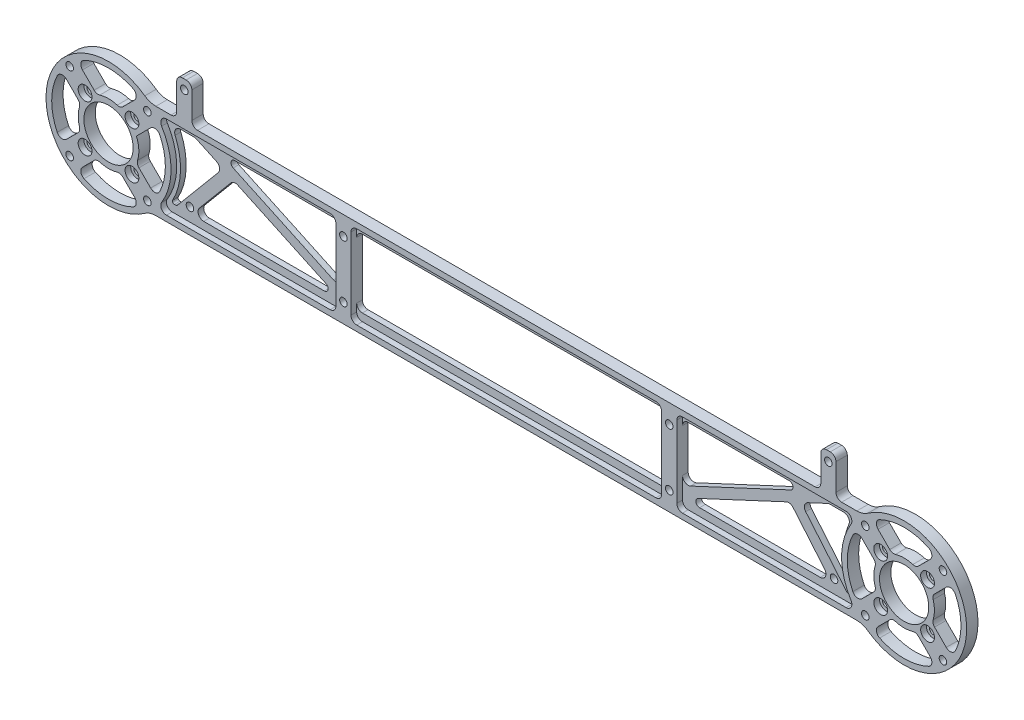
SolidWorks part; units mm, degrees
material "6061 合金"
ref_plane "前视基准面" through (0, 0, 0) normal (0, 0, 1) x (1, 0, 0)
ref_plane "上视基准面" through (0, 0, 0) normal (0, 1, 0) x (1, 0, 0)
ref_plane "右视基准面" through (0, 0, 0) normal (1, 0, 0) x (0, 0, -1)
sketch "草图1" plane through (0, 0, 0) normal (0, 0, 1) x (1, 0, 0)
  line L0 (0, 45.7031) -> (0, -72.9118) construction
  line L1 (-42.6422, 0) -> (420, 0) construction
  line L2 (0, 0) -> (-20.5061, 20.5061) construction
  line L3 (21.5407, 25) -> (398.4593, 25)
  line L4 (21.5407, -25) -> (398.4593, -25)
  line L5 (210, 25) -> (210, -95.809) construction
  line L7 (30.0167, 18) -> (120, 18)
  line L8 (30.0167, 18) -> (30.0167, -18) construction
  line L9 (30.0167, -18) -> (120, -18)
  line L10 (120, 18) -> (120, -18)
  line L11 (30.0167, 18) -> (120, -18) construction
  line L12 (30.0167, -18) -> (120, 18) construction
  line L13 (300, 18) -> (389.9833, 18)
  line L14 (300, 18) -> (300, -18)
  line L15 (300, -18) -> (389.9833, -18)
  line L16 (389.9833, 18) -> (389.9833, -18) construction
  line L17 (300, 18) -> (389.9833, -18) construction
  line L18 (300, -18) -> (389.9833, 18) construction
  line L19 (128, 18) -> (292, 18)
  line L20 (128, 18) -> (128, -18)
  line L21 (128, -18) -> (292, -18)
  line L22 (292, 18) -> (292, -18)
  line L23 (128, 18) -> (292, -18) construction
  line L24 (128, -18) -> (292, 18) construction
  circle A0 centre (0, 0) radius 29 construction
  circle A1 centre (-20.5061, 20.5061) radius 2
  circle A5 centre (20.5061, 20.5061) radius 2
  circle A6 centre (20.5061, -20.5061) radius 2
  circle A7 centre (-20.5061, -20.5061) radius 2
  circle A8 centre (0, 0) radius 13
  arc A9 (21.5407, 25) -> (21.5407, -25) centre (0, 0) ccw
  circle A10 centre (440.5061, 20.5061) radius 2
  arc A11 (398.4593, -25) -> (398.4593, 25) centre (420, 0) ccw
  circle A12 centre (420, 0) radius 13
  circle A13 centre (440.5061, -20.5061) radius 2
  circle A14 centre (399.4939, -20.5061) radius 2
  circle A15 centre (399.4939, 20.5061) radius 2
  arc A17 (389.9833, 18) -> (389.9833, -18) centre (420, 0) ccw
  arc A18 (30.0167, -18) -> (30.0167, 18) centre (0, 0) ccw
  circle A19 centre (-12.3744, 12.3744) radius 2
  circle A20 centre (12.3744, 12.3744) radius 2
  circle A21 centre (12.3744, -12.3744) radius 2
  circle A22 centre (-12.3744, -12.3744) radius 2
  circle A23 centre (432.3744, 12.3744) radius 2
  circle A24 centre (432.3744, -12.3744) radius 2
  circle A25 centre (407.6256, -12.3744) radius 2
  circle A26 centre (407.6256, 12.3744) radius 2
  point P6 (344.9917, 0)
  point P18 (0, 0)
  point P31 (75.0083, 0)
  point P42 (210, 0)
  point P58 (0, 0)
  dimension "D1" = 16
  dimension "D3" = 4
  dimension "D5" = 26
  dimension "D6" = 4
  dimension "D8" = 420
  dimension "D11" = 35
  dimension "D14" = 58
  dimension "D15" = 33
  dimension "D16" = 17.5
  dimension "D17" = 4
  dimension "D20" = 420
  dimension "D2" = 45
  dimension "D9" = 50
  dimension "D10" = 7
  dimension "D12" = 8
  dimension "D13" = 120
  dimension "D7" = 2
  dimension "D19" = 2
  dimension "D4" = 4
  dimension "D18" = 4
extrude "凸台-拉伸1" add sketch "草图1" along normal blind 6
fillet "圆角1" [suppressed] radius 3
sketch "草图2" plane through (0, 0, 6) normal (0, 0, 1) x (1, 0, 0)
  line L0 (210, 25) -> (210, -72.3198) construction
  line L1 (398.4593, 25) -> (21.5407, 25) construction
  line L2 (124, -22.0435) -> (124, 29.2031) construction
  line L3 (128, 18) -> (128, -18) construction
  line L4 (120, 0) -> (300, 0) construction
  line L5 (120, -18) -> (120, 18) construction
  line L6 (300, 18) -> (300, -18) construction
  circle A0 centre (124, 15) radius 2
  circle A1 centre (124, -15) radius 2
  circle A2 centre (296, 15) radius 2
  circle A3 centre (296, -15) radius 2
  dimension "D1" = 4
  dimension "D3" = 30
  dimension "D2" = 4
extrude "切除-拉伸1" cut sketch "草图2" against normal through all
sketch "草图3" plane through (0, 0, 6) normal (0, 0, 1) x (1, 0, 0)
  line L0 (210, -25) -> (210, 69.7704) construction
  line L1 (21.5407, -25) -> (398.4593, -25) construction
  line L2 (398.4593, 25) -> (21.5407, 25) construction
  line L3 (36, 25) -> (44, 25)
  line L4 (36, 25) -> (36, 45)
  line L5 (36, 45) -> (44, 45)
  line L6 (44, 25) -> (44, 45)
  line L7 (0, 0) -> (420, 0) construction
  line L16 (384, 25) -> (376, 25)
  line L17 (384, 25) -> (384, 45)
  line L18 (384, 45) -> (376, 45)
  line L19 (376, 25) -> (376, 45)
  line L20 (40, 45) -> (40, -45) construction
  line L21 (380, 45) -> (380, -45) construction
  line L32 (120, -12.4831) -> (54.6288, 18)
  line L33 (120, -18) -> (120, 18) construction
  line L34 (120, 18) -> (30.0167, 18) construction
  line L35 (54.6288, 18) -> (42.7978, 18)
  line L36 (42.7978, 18) -> (57.4676, 11.1593)
  line L37 (120, -18) -> (120, -12.4831)
  line L38 (57.4676, 11.1593) -> (33, -18)
  line L39 (30.0167, -18) -> (120, -18) construction
  line L40 (33, -18) -> (40.8324, -18)
  line L41 (40.8324, -18) -> (63.0973, 8.5342)
  line L43 (63.0973, 8.5342) -> (120, -18)
  line L44 (387, -18) -> (379.1676, -18)
  line L45 (362.5324, 11.1593) -> (387, -18)
  line L46 (377.2022, 18) -> (362.5324, 11.1593)
  line L47 (365.3712, 18) -> (377.2022, 18)
  line L48 (300, -12.4831) -> (365.3712, 18)
  line L49 (300, -18) -> (300, -12.4831)
  line L50 (356.9027, 8.5342) -> (300, -18)
  line L51 (379.1676, -18) -> (356.9027, 8.5342)
  circle A1 centre (380, 40) radius 2
  circle A2 centre (40, 40) radius 2
  point P31 (40, 45)
  point P32 (380, 45)
  dimension "D4" = 4
  dimension "D5" = 5
  dimension "D1" = 8
  dimension "D2" = 20
  dimension "D3" = 340
  dimension "D6" = 5
  dimension "D7" = 6
  dimension "D8" = 87
  dimension "D9" = 25
  dimension "D10" = 50
extrude "凸台-拉伸2" add sketch "草图3" against normal up to surface (6 mm away) up to face at (126, -15, 0)
fillet "圆角2" radius 3 8 edges at (36, 45, 3) (44, 45, 3) (376, 45, 3) (384, 45, 3) (376, 25, 3) (384, 25, 3) (44, 25, 3) (36, 25, 3)
sketch "草图4" plane through (0, 0, 6) normal (0, 0, 1) x (1, 0, 0)
  line L0 (40, 40) -> (40, -25) construction
  line L1 (21.5407, -25) -> (398.4593, -25) construction
  line L2 (380, 40) -> (380, -25) construction
  circle A0 centre (40, -15) radius 2
  circle A1 centre (380, -15) radius 2
  dimension "D1" = 4
  dimension "D2" = 10
extrude "切除-拉伸2" cut sketch "草图4" against normal through all
fillet "圆角3" radius 3 18 edges at (389.9833, 18, 3) (377.2022, 18, 3) (362.5324, 11.1593, 3) (379.1676, -18, 3) (356.9027, 8.5342, 3) (300, -12.4831, 3) (300, 18, 3) (292, 18, 3) (292, -18, 3) (128, 18, 3) (128, -18, 3) (120, -12.4831, 3) (120, 18, 3) (63.0973, 8.5342, 3) (57.4676, 11.1593, 3) (42.7978, 18, 3) (30.0167, 18, 3) (40.8324, -18, 3)
fillet "圆角4" radius 2 4 edges at (300, -18, 3) (365.3712, 18, 3) (54.6288, 18, 3) (120, -18, 3)
sketch "草图9" plane through (0, 0, 6) normal (0, 0, 1) x (1, 0, 0)
  line L2 (373, 22) -> (47, 22)
  line L3 (395.4033, 22) -> (300, 22)
  line L4 (300, 15) -> (300, -7.7741) construction
  line L5 (21.5407, -22) -> (398.4593, -22)
  line L6 (24.5967, -22) -> (120, -22)
  line L8 (120, 22) -> (120, -22)
  line L10 (128, 22) -> (128, -22)
  line L12 (292, 22) -> (292, -22)
  line L14 (300, 22) -> (300, -22)
  line L15 (292, -15) -> (292, 15) construction
  line L16 (128, 15) -> (128, -15) construction
  line L17 (120, -7.7741) -> (120, 15) construction
  line L18 (120, 22) -> (24.5967, 22)
  line L19 (128, -22) -> (292, -22)
  line L20 (292, 22) -> (128, 22)
  line L21 (300, -22) -> (395.4033, -22)
  arc A0 (24.5967, -22) -> (24.5967, 22) centre (0, 0) ccw
  arc A1 (395.4033, 22) -> (395.4033, -22) centre (420, 0) ccw
  circle A2 centre (0, 0) radius 13 construction
  dimension "D1" = 20
  dimension "D4" = 33
  dimension "D2" = 3
  dimension "D3" = 3
extrude "切除-拉伸3" cut sketch "草图9" against normal blind 3
fillet "圆角5" radius 3 12 edges at (395.4033, -22, 4.5) (395.4033, 22, 4.5) (300, 22, 4.5) (300, -22, 4.5) (292, -22, 4.5) (292, 22, 4.5) (128, 22, 4.5) (128, -22, 4.5) (120, -22, 4.5) (120, 22, 4.5) (24.5967, -22, 4.5) (24.5967, 22, 4.5)
sketch "草图10" plane through (0, 0, 6) normal (0, 0, 1) x (1, 0, 0)
  line L2 (0, 0) -> (-20.5061, 20.5061) construction
  line L19 (0, 0) -> (0, 36.5835) construction
  line L20 (0, 0) -> (20.5061, 20.5061) construction
  line L21 (-16.542, 25.0273) -> (-6.2454, 14.7307)
  line L22 (16.542, 25.0273) -> (6.2454, 14.7307)
  line L23 (25.0273, -16.542) -> (14.7307, -6.2454)
  line L24 (25.0273, 16.542) -> (14.7307, 6.2454)
  line L25 (-16.542, -25.0273) -> (-6.2454, -14.7307)
  line L26 (16.542, -25.0273) -> (6.2454, -14.7307)
  line L27 (-25.0273, 16.542) -> (-14.7307, 6.2454)
  line L28 (-25.0273, -16.542) -> (-14.7307, -6.2454)
  line L29 (445.0273, -16.542) -> (434.7307, -6.2454)
  line L30 (445.0273, 16.542) -> (434.7307, 6.2454)
  line L31 (436.542, 25.0273) -> (426.2454, 14.7307)
  line L32 (403.458, 25.0273) -> (413.7546, 14.7307)
  line L33 (403.458, -25.0273) -> (413.7546, -14.7307)
  line L34 (436.542, -25.0273) -> (426.2454, -14.7307)
  line L35 (394.9727, 16.542) -> (405.2693, 6.2454)
  line L36 (394.9727, -16.542) -> (405.2693, -6.2454)
  arc A18 (6.2454, 14.7307) -> (-6.2454, 14.7307) centre (0, 0) ccw
  arc A19 (16.542, 25.0273) -> (-16.542, 25.0273) centre (0, 0) ccw
  circle A20 centre (0, 0) radius 13 construction
  arc A21 (21.5407, 25) -> (21.5407, -25) centre (0, 0) ccw construction
  arc A22 (14.7307, -6.2454) -> (14.7307, 6.2454) centre (0, 0) ccw
  arc A23 (25.0273, -16.542) -> (25.0273, 16.542) centre (0, 0) ccw
  arc A24 (-6.2454, -14.7307) -> (6.2454, -14.7307) centre (0, 0) ccw
  arc A25 (-16.542, -25.0273) -> (16.542, -25.0273) centre (0, 0) ccw
  arc A26 (-14.7307, 6.2454) -> (-14.7307, -6.2454) centre (0, 0) ccw
  arc A27 (-25.0273, 16.542) -> (-25.0273, -16.542) centre (0, 0) ccw
  arc A28 (434.7307, -6.2454) -> (434.7307, 6.2454) centre (420, 0) ccw
  arc A29 (445.0273, -16.542) -> (445.0273, 16.542) centre (420, 0) ccw
  arc A30 (426.2454, 14.7307) -> (413.7546, 14.7307) centre (420, 0) ccw
  arc A31 (436.542, 25.0273) -> (403.458, 25.0273) centre (420, 0) ccw
  arc A32 (413.7546, -14.7307) -> (426.2454, -14.7307) centre (420, 0) ccw
  arc A33 (403.458, -25.0273) -> (436.542, -25.0273) centre (420, 0) ccw
  arc A34 (405.2693, 6.2454) -> (405.2693, -6.2454) centre (420, 0) ccw
  arc A35 (394.9727, 16.542) -> (394.9727, -16.542) centre (420, 0) ccw
  circle A36 centre (420, 0) radius 13 construction
  point P29 (0, 0)
  dimension "D1" = 3
  dimension "D2" = 3
  dimension "D3" = 6
  dimension "D5" = 2
  dimension "D4" = 4
extrude "切除-拉伸4" cut sketch "草图10" against normal through all
fillet "圆角6" radius 3 31 edges at (405.2693, -6.2454, 3) (394.9727, -16.542, 3) (403.458, -25.0273, 3) (436.542, -25.0273, 3) (445.0273, -16.542, 3) (434.7307, -6.2454, 3) (434.7307, 6.2454, 3) (426.2454, -14.7307, 3) (413.7546, -14.7307, 3) (394.9727, 16.542, 3) (405.2693, 6.2454, 3) (445.0273, 16.542, 3) (413.7546, 14.7307, 3) (426.2454, 14.7307, 3) (436.542, 25.0273, 3) (403.458, 25.0273, 3) (-25.0273, 16.542, 3) (-14.7307, 6.2454, 3) (-14.7307, -6.2454, 3) (-25.0273, -16.542, 3) (-16.542, -25.0273, 3) (-6.2454, -14.7307, 3) (16.542, -25.0273, 3) (6.2454, -14.7307, 3) (14.7307, -6.2454, 3) (25.0273, -16.542, 3) (25.0273, 16.542, 3) (16.542, 25.0273, 3) (6.2454, 14.7307, 3) (-6.2454, 14.7307, 3) (-16.542, 25.0273, 3)
sketch "草图12" plane through (0, 0, 6) normal (0, 0, 1) x (1, 0, 0)
  circle A0 centre (-12.3744, 12.3744) radius 3.65
  circle A1 centre (12.3744, 12.3744) radius 3.65
  circle A3 centre (-12.3744, -12.3744) radius 3.65
  circle A4 centre (12.3744, -12.3744) radius 3.65
  circle A5 centre (407.6256, 12.3744) radius 3.65
  circle A6 centre (432.3744, 12.3744) radius 3.65
  circle A7 centre (432.3744, -12.3744) radius 3.65
  circle A8 centre (407.6256, -12.3744) radius 3.65
  dimension "D1" = 7.3
extrude "切除-拉伸5" cut sketch "草图12" against normal blind 3
fillet "圆角7" radius 10 4 edges at (398.4593, 25, 3) (398.4593, -25, 3) (21.5407, -25, 3) (21.5407, 25, 3)
fillet "圆角8" radius 1 4 edges at (33, -18, 1.5) (30.0167, -18, 1.5) (387, -18, 1.5) (389.9833, -18, 1.5)
